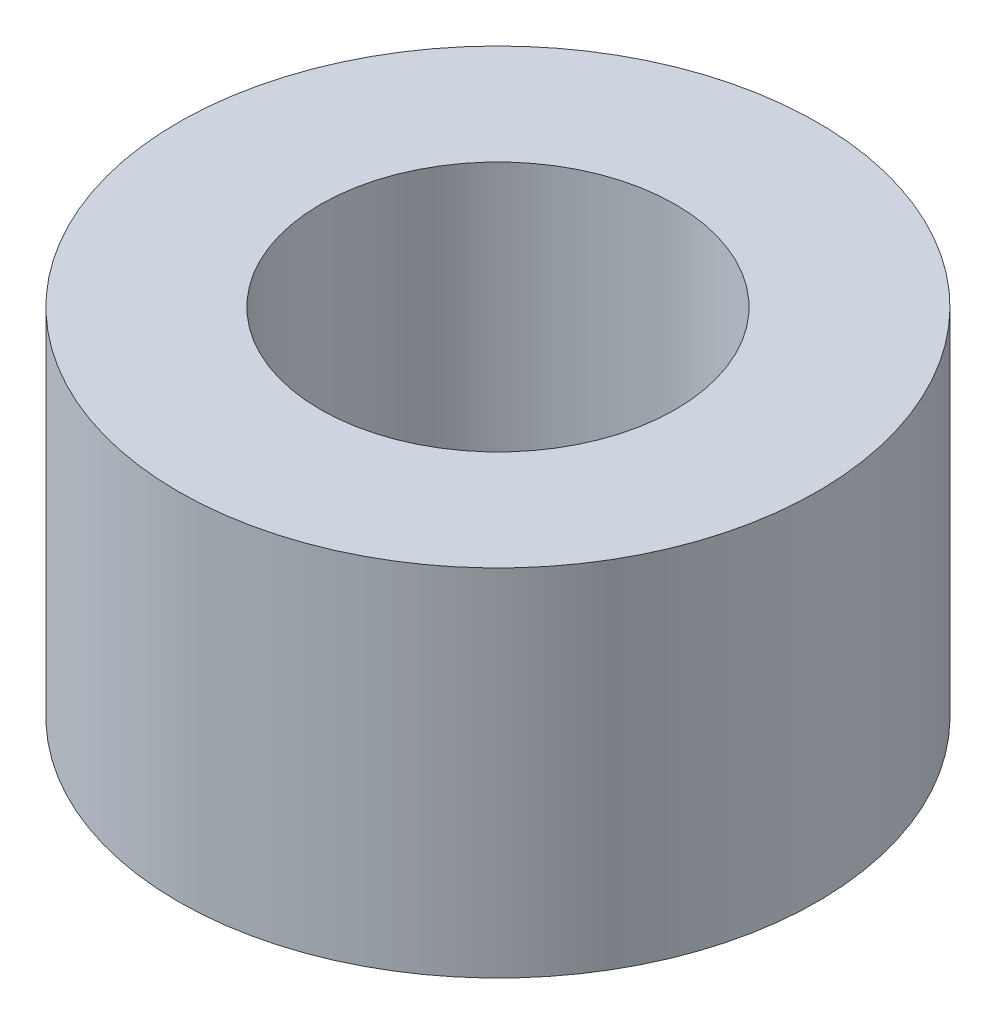
SolidWorks part; units mm, degrees
ref_plane "Front Plane" through (0, 0, 0) normal (0, 0, 1) x (1, 0, 0)
ref_plane "Top Plane" through (0, 0, 0) normal (0, 1, 0) x (1, 0, 0)
ref_plane "Right Plane" through (0, 0, 0) normal (1, 0, 0) x (0, 0, -1)
sketch "Sketch1" plane through (0, 0, 0) normal (0, 1, 0) x (1, 0, 0)
  circle A0 centre (0, 0) radius 2.5
  circle A1 centre (0, 0) radius 4.5
  dimension "D1" = 5
  dimension "D2" = 2
extrude "Boss-Extrude1" add sketch "Sketch1" along normal blind 5
